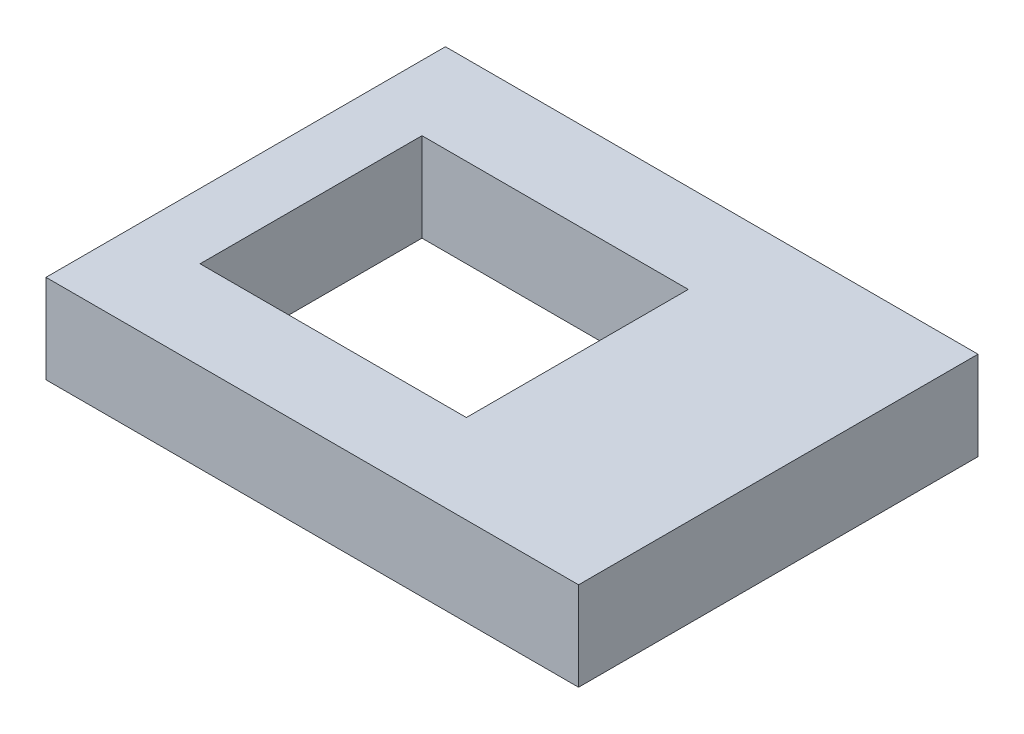
SolidWorks part; units mm, degrees
material "AISI 304"
ref_plane "Front Plane" through (0, 0, 0) normal (0, 0, 1) x (1, 0, 0)
ref_plane "Top Plane" through (0, 0, 0) normal (0, 1, 0) x (1, 0, 0)
ref_plane "Right Plane" through (0, 0, 0) normal (1, 0, 0) x (0, 0, -1)
sketch "Sketch1" plane through (0, 0, 0) normal (0, 1, 0) x (1, 0, 0)
  line L1 (-76.2, -57.15) -> (76.2, -57.15)
  line L2 (-76.2, -57.15) -> (-76.2, 57.15)
  line L3 (-76.2, 57.15) -> (76.2, 57.15)
  line L4 (76.2, -57.15) -> (76.2, 57.15)
  line L5 (-76.2, -57.15) -> (76.2, 57.15) construction
  line L6 (-76.2, 57.15) -> (76.2, -57.15) construction
  point P0 (0, 0)
  dimension "D1" = 114.3
  dimension "D2" = 152.4
extrude "Boss-Extrude1" add sketch "Sketch1" along normal blind 25.4
sketch "Sketch2" plane through (0, 25.4, 0) normal (0, 1, 0) x (1, 0, 0)
  line L0 (-76.2, -57.15) -> (76.2, -57.15) construction
  line L1 (-57.5071, -31.75) -> (18.6929, -31.75)
  line L2 (-57.5071, -31.75) -> (-57.5071, 31.75)
  line L3 (-57.5071, 31.75) -> (18.6929, 31.75)
  line L4 (18.6929, -31.75) -> (18.6929, 31.75)
  line L5 (-57.5071, -31.75) -> (18.6929, 31.75) construction
  line L6 (-57.5071, 31.75) -> (18.6929, -31.75) construction
  point P0 (-19.4071, 0)
  dimension "D1" = 63.5
  dimension "D2" = 76.2
  dimension "D3" = 57.15
extrude "Cut-Extrude1" cut sketch "Sketch2" against normal through all
